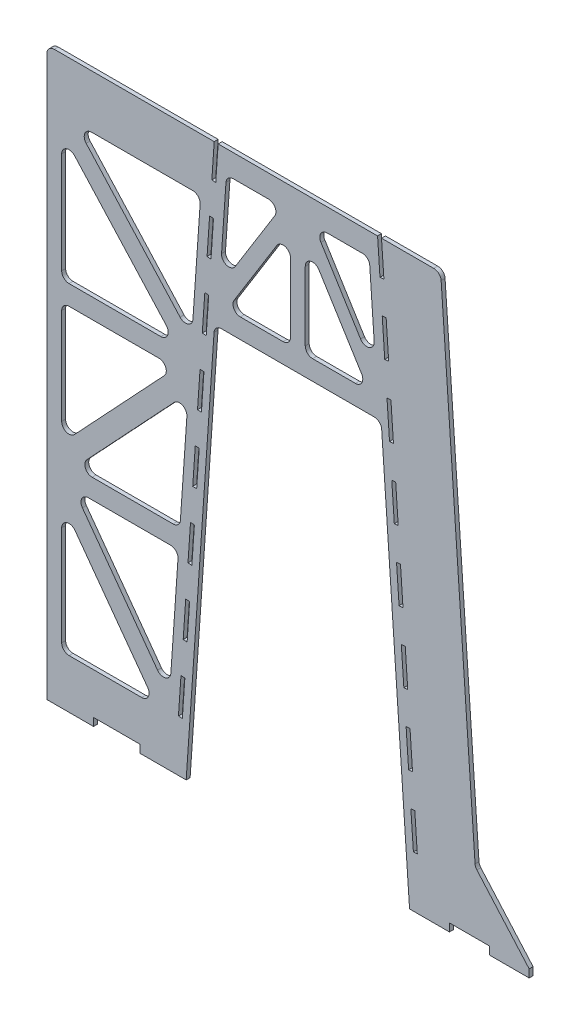
SolidWorks part; units mm, degrees
material "A-Glass Fiber"
ref_plane "Front Plane" through (0, 0, 0) normal (0, 0, 1) x (1, 0, 0)
ref_plane "Top Plane" through (0, 0, 0) normal (0, 1, 0) x (1, 0, 0)
ref_plane "Right Plane" through (0, 0, 0) normal (1, 0, 0) x (0, 0, -1)
sketch "Sketch1" plane through (0, 0, 0) normal (0, 0, 1) x (1, 0, 0)
  line L0 (-288.2759, 0) -> (288.2759, 0) construction
  line L1 (-215.8925, 1463.04) -> (215.8925, 1463.04)
  line L2 (0, 0) -> (0, 1733.4513) construction
  line L3 (19.05, 1104.9) -> (205.1391, 1104.9)
  line L4 (202.3135, 1145.5664) -> (41.4731, 1404.62)
  line L5 (205.1391, 1104.9) -> (19.05, 1404.62) construction
  line L6 (205.1391, 1104.9) -> (184.3133, 1404.62)
  line L7 (182.716, 1104.9) -> (19.05, 1368.5047)
  line L8 (19.05, 1404.62) -> (19.05, 1104.9)
  line L9 (184.3133, 1404.62) -> (19.05, 1404.62)
  line L10 (205.7153, 1463.04) -> (307.3735, 0)
  line L11 (317.5154, 0.5076) -> (215.8925, 1463.04)
  line L12 (317.5154, 0.5076) -> (317.5507, 0)
  line L13 (288.2759, 0) -> (215.0326, 1054.1)
  line L14 (476.8528, 0) -> (391.1675, 0) construction
  line L15 (266.6925, 1463.04) -> (368.5375, 1463.04)
  line L16 (368.5375, 1463.04) -> (457.7693, 178.8376)
  line L81 (215.8925, 1463.04) -> (266.6925, 1463.04)
  line L82 (-215.8925, 1463.04) -> (-647.7182, 1463.04)
  line L88 (317.5507, 0) -> (307.3718, 0)
  line L90 (215.0326, 1054.1) -> (-215.0326, 1054.1)
  line L92 (307.3718, 0) -> (288.2759, 0)
  line L93 (-288.2759, 0) -> (-215.0326, 1054.1)
  line L94 (-307.3735, 0) -> (-288.2759, 0)
  line L97 (-317.5507, 0) -> (-307.3735, 0)
  line L98 (-317.5154, 0.5076) -> (-317.5507, 0)
  line L99 (-317.5154, 0.5076) -> (-215.8925, 1463.04)
  line L100 (-205.7153, 1463.04) -> (-307.3735, 0)
  line L124 (-184.3133, 1404.62) -> (-19.05, 1404.62)
  line L125 (-19.05, 1404.62) -> (-19.05, 1104.9)
  line L126 (-182.716, 1104.9) -> (-19.05, 1368.5047)
  line L127 (-205.1391, 1104.9) -> (-19.05, 1404.62) construction
  line L128 (-202.3135, 1145.5664) -> (-41.4731, 1404.62)
  line L129 (-205.1391, 1104.9) -> (-184.3133, 1404.62)
  line L130 (-19.05, 1104.9) -> (-205.1391, 1104.9)
  line L131 (-317.5507, 0) -> (-647.7182, 0)
  line L132 (-647.7182, 0) -> (-647.7182, 1463.04)
  line L133 (-647.7182, 0) -> (-317.5507, 0)
  line L134 (-308.7262, 127) -> (-647.7182, 127)
  line L135 (-647.7182, 1325.88) -> (-225.423, 1325.88)
  line L136 (317.5507, 0) -> (368.3507, 0)
  line L137 (368.3507, 0) -> (266.6925, 1463.04)
  line L138 (368.3507, 0) -> (317.5507, 0)
  line L139 (-250.8842, 1325.88) -> (-334.1875, 127)
  line L140 (-609.6182, 127) -> (-609.6182, 1325.88)
  line L141 (-306.1844, 530.0133) -> (-609.6182, 530.0133)
  line L142 (-278.1813, 933.0267) -> (-609.6182, 933.0267)
  line L143 (-304.4195, 555.4133) -> (-609.6182, 555.4133)
  line L144 (-307.9493, 504.6133) -> (-609.6182, 504.6133)
  line L145 (-279.9462, 907.6267) -> (-609.6182, 907.6267)
  line L146 (-276.4164, 958.4267) -> (-609.6182, 958.4267)
  line L147 (-334.1875, 127) -> (-609.6182, 504.6133) construction
  line L148 (-609.6182, 555.4133) -> (-279.9462, 907.6267) construction
  line L149 (-276.4164, 958.4267) -> (-609.6182, 1325.88) construction
  line L150 (-331.453, 166.3535) -> (-578.1794, 504.6133)
  line L151 (-574.8276, 555.4133) -> (-282.736, 867.4768)
  line L152 (-273.976, 993.5478) -> (-575.3304, 1325.88)
  line L153 (-365.6263, 127) -> (-609.6182, 461.511)
  line L154 (-609.6182, 592.5827) -> (-314.7368, 907.6267)
  line L155 (-310.7042, 958.4267) -> (-609.6182, 1288.0676)
  line L156 (368.3507, 0) -> (596.9507, 0)
  line L157 (596.9507, 0) -> (596.9507, 20.32)
  line L158 (596.9507, 20.32) -> (347.1719, 304.8)
  point P0 (0, 0)
  point P3 (0, 0)
  point P106 (0, 0)
  point P118 (0, 1054.1)
  dimension "D6" = 25.4
  dimension "D7" = 50.8
  dimension "D8" = 58.42
  dimension "D9" = 19.05
  dimension "D10" = 647.7182
  dimension "D11" = 10.1527
  dimension "D12" = 25.4
  dimension "D13" = 25.4
  dimension "D14" = 25.4
  dimension "D15" = 25.4
  dimension "D16" = 25.4
  dimension "D17" = 25.4
  dimension "D18" = 1463.04
  dimension "D19" = 288.2759
  dimension "D20" = 29.2044
  dimension "D21" = 101.6
  dimension "D22" = 19.05
  dimension "D23" = 19.05
  dimension "D24" = 1054.1
  dimension "D25" = 20.32
  dimension "D37" = 127
  dimension "D38" = 50.8
  dimension "D39" = 25.4
  dimension "D40" = 38.1
  dimension "D41" = 403.0133
  dimension "D42" = 403.0133
  dimension "D43" = 25.4
  dimension "D44" = 25.4
  dimension "D45" = 25.4
  dimension "D46" = 25.4
  dimension "D47" = 279.4
  dimension "D48" = 304.8
  dimension "D49" = 50.8
  dimension "D52" = 137.16
extrude "Boss-Extrude1" add sketch "Sketch1" along normal blind 10.16
fillet "Fillet1" radius 19.05 35 edges at (-215.0326, 1054.1, 5.08) (215.0326, 1054.1, 5.08) (-202.3135, 1145.5664, 5.08) (-19.05, 1104.9, 5.08) (-182.716, 1104.9, 5.08) (-19.05, 1368.5047, 5.08) (-41.4731, 1404.62, 5.08) (-184.3133, 1404.62, 5.08) (-647.7182, 1463.04, 5.08) (-250.8842, 1325.88, 5.08) (-575.3304, 1325.88, 5.08) (-273.976, 993.5478, 5.08) (-609.6182, 958.4267, 5.08) (-609.6182, 1288.0676, 5.08) (-310.7042, 958.4267, 5.08) (-609.6182, 592.5827, 5.08) (-314.7368, 907.6267, 5.08) (-609.6182, 907.6267, 5.08) (-574.8276, 555.4133, 5.08) (-304.4195, 555.4133, 5.08) (-282.736, 867.4768, 5.08) (-307.9493, 504.6133, 5.08) (-331.453, 166.3535, 5.08) (-578.1794, 504.6133, 5.08) (-609.6182, 461.511, 5.08) (-365.6263, 127, 5.08) (-609.6182, 127, 5.08) (19.05, 1104.9, 5.08) (184.3133, 1404.62, 5.08) (41.4731, 1404.62, 5.08) (182.716, 1104.9, 5.08) (19.05, 1368.5047, 5.08) (202.3135, 1145.5664, 5.08) (457.7693, 178.8376, 5.08) (368.5375, 1463.04, 5.08)
sketch "Sketch2" plane through (0, 0, 10.16) normal (0, 0, 1) x (1, 0, 0)
  line L28 (215.8818, 1463.04) -> (205.7153, 1463.04) construction
  line L29 (205.7153, 1463.04) -> (211.9231, 1373.6642) construction
  line L30 (211.9231, 1373.6642) -> (222.0407, 1374.3669) construction
  line L31 (222.0407, 1374.3669) -> (215.8818, 1463.04) construction
  line L32 (217.7192, 1290.2141) -> (224.241, 1196.3181) construction
  line L33 (224.241, 1196.3181) -> (234.3587, 1197.0208) construction
  line L34 (234.3587, 1197.0208) -> (227.8369, 1290.9169) construction
  line L35 (227.8369, 1290.9169) -> (217.7192, 1290.2141) construction
  line L64 (230.039, 1112.8414) -> (236.5589, 1018.9719) construction
  line L65 (236.5589, 1018.9719) -> (246.6766, 1019.6747) construction
  line L66 (246.6766, 1019.6747) -> (240.1567, 1113.5442) construction
  line L67 (240.1567, 1113.5442) -> (230.039, 1112.8414) construction
  line L68 (242.3588, 935.4688) -> (248.8768, 841.6258) construction
  line L69 (248.8768, 841.6258) -> (258.9945, 842.3285) construction
  line L70 (258.9945, 842.3285) -> (252.4764, 936.1715) construction
  line L71 (252.4764, 936.1715) -> (242.3588, 935.4688) construction
  line L72 (254.6785, 758.0961) -> (261.1947, 664.2796) construction
  line L73 (261.1947, 664.2796) -> (271.3124, 664.9824) construction
  line L74 (271.3124, 664.9824) -> (264.7962, 758.7989) construction
  line L75 (264.7962, 758.7989) -> (254.6785, 758.0961) construction
  line L76 (266.9983, 580.7234) -> (273.5126, 486.9335) construction
  line L77 (273.5126, 486.9335) -> (283.6303, 487.6362) construction
  line L78 (283.6303, 487.6362) -> (277.1159, 581.4262) construction
  line L79 (277.1159, 581.4262) -> (266.9983, 580.7234) construction
  line L80 (279.318, 403.3508) -> (285.8305, 309.5874) construction
  line L81 (285.8305, 309.5874) -> (295.9482, 310.2901) construction
  line L82 (295.9482, 310.2901) -> (289.4357, 404.0535) construction
  line L83 (289.4357, 404.0535) -> (279.318, 403.3508) construction
  line L84 (291.6378, 225.9781) -> (298.1484, 132.2412) construction
  line L85 (298.1484, 132.2412) -> (308.2661, 132.944) construction
  line L86 (308.2661, 132.944) -> (301.7555, 226.6808) construction
  line L87 (301.7555, 226.6808) -> (291.6378, 225.9781) construction
  line L116 (215.8818, 1463.04) -> (205.7153, 1463.04)
  line L117 (205.7153, 1463.04) -> (211.9231, 1373.6642)
  line L118 (211.9231, 1373.6642) -> (222.0407, 1374.3669)
  line L119 (222.0407, 1374.3669) -> (215.8818, 1463.04)
  line L120 (217.7192, 1290.2141) -> (224.241, 1196.3181)
  line L121 (224.241, 1196.3181) -> (234.3587, 1197.0208)
  line L122 (234.3587, 1197.0208) -> (227.8369, 1290.9169)
  line L123 (227.8369, 1290.9169) -> (217.7192, 1290.2141)
  line L152 (230.039, 1112.8414) -> (236.5589, 1018.9719)
  line L153 (236.5589, 1018.9719) -> (246.6766, 1019.6747)
  line L154 (246.6766, 1019.6747) -> (240.1567, 1113.5442)
  line L155 (240.1567, 1113.5442) -> (230.039, 1112.8414)
  line L156 (242.3588, 935.4688) -> (248.8768, 841.6258)
  line L157 (248.8768, 841.6258) -> (258.9945, 842.3285)
  line L158 (258.9945, 842.3285) -> (252.4764, 936.1715)
  line L159 (252.4764, 936.1715) -> (242.3588, 935.4688)
  line L160 (254.6785, 758.0961) -> (261.1947, 664.2796)
  line L161 (261.1947, 664.2796) -> (271.3124, 664.9824)
  line L162 (271.3124, 664.9824) -> (264.7962, 758.7989)
  line L163 (264.7962, 758.7989) -> (254.6785, 758.0961)
  line L164 (266.9983, 580.7234) -> (273.5126, 486.9335)
  line L165 (273.5126, 486.9335) -> (283.6303, 487.6362)
  line L166 (283.6303, 487.6362) -> (277.1159, 581.4262)
  line L167 (277.1159, 581.4262) -> (266.9983, 580.7234)
  line L168 (279.318, 403.3508) -> (285.8305, 309.5874)
  line L169 (285.8305, 309.5874) -> (295.9482, 310.2901)
  line L170 (295.9482, 310.2901) -> (289.4357, 404.0535)
  line L171 (289.4357, 404.0535) -> (279.318, 403.3508)
  line L172 (291.6378, 225.9781) -> (298.1484, 132.2412)
  line L173 (298.1484, 132.2412) -> (308.2661, 132.944)
  line L174 (308.2661, 132.944) -> (301.7555, 226.6808)
  line L175 (301.7555, 226.6808) -> (291.6378, 225.9781)
  line L194 (-134.539, 20.32) -> (-288.2759, 20.32) construction
  line L195 (-647.7182, 0) -> (-527.4335, 0)
  line L196 (-647.7182, 0) -> (-647.7182, 20.32)
  line L197 (-647.7182, 20.32) -> (-527.4335, 20.32)
  line L198 (-527.4335, 0) -> (-527.4335, 20.32)
  line L199 (-288.2759, 0) -> (-216.2645, 1036.3705) construction
  line L200 (-527.4335, 0) -> (-407.1487, 0)
  line L201 (-527.4335, 0) -> (-527.4335, 20.32)
  line L202 (-527.4335, 20.32) -> (-407.1487, 20.32)
  line L203 (-407.1487, 0) -> (-407.1487, 20.32)
  line L204 (-407.1487, 0) -> (-286.864, 0)
  line L205 (-407.1487, 0) -> (-407.1487, 20.32)
  line L206 (-407.1487, 20.32) -> (-286.864, 20.32)
  line L207 (-286.864, 0) -> (-286.864, 20.32)
  line L213 (288.2759, 20.32) -> (134.539, 20.32) construction
  line L230 (288.2759, 0) -> (391.1675, 0)
  line L231 (288.2759, 0) -> (288.2759, 20.32)
  line L232 (288.2759, 20.32) -> (391.1675, 20.32)
  line L233 (391.1675, 0) -> (391.1675, 20.32)
  line L235 (391.1675, 0) -> (494.0591, 0)
  line L236 (391.1675, 0) -> (391.1675, 20.32)
  line L237 (391.1675, 20.32) -> (494.0591, 20.32)
  line L238 (494.0591, 0) -> (494.0591, 20.32)
  line L239 (494.0591, 0) -> (596.9507, 0)
  line L240 (494.0591, 0) -> (494.0591, 20.32)
  line L241 (494.0591, 20.32) -> (596.9507, 20.32)
  line L242 (596.9507, 0) -> (596.9507, 20.32)
  line L254 (-205.7153, 1463.04) -> (-215.8818, 1463.04) construction
  line L255 (-215.8818, 1463.04) -> (-222.0407, 1374.3669) construction
  line L256 (-222.0407, 1374.3669) -> (-211.9231, 1373.6642) construction
  line L257 (-211.9231, 1373.6642) -> (-205.7153, 1463.04) construction
  line L258 (-224.241, 1196.3181) -> (-217.7192, 1290.2141) construction
  line L259 (-217.7192, 1290.2141) -> (-227.8369, 1290.9169) construction
  line L260 (-227.8369, 1290.9169) -> (-234.3587, 1197.0208) construction
  line L261 (-234.3587, 1197.0208) -> (-224.241, 1196.3181) construction
  line L262 (-236.5589, 1018.9719) -> (-230.039, 1112.8414) construction
  line L263 (-230.039, 1112.8414) -> (-240.1567, 1113.5442) construction
  line L264 (-240.1567, 1113.5442) -> (-246.6766, 1019.6747) construction
  line L265 (-246.6766, 1019.6747) -> (-236.5589, 1018.9719) construction
  line L266 (-248.8768, 841.6258) -> (-242.3588, 935.4688) construction
  line L267 (-242.3588, 935.4688) -> (-252.4764, 936.1715) construction
  line L268 (-252.4764, 936.1715) -> (-258.9945, 842.3285) construction
  line L269 (-258.9945, 842.3285) -> (-248.8768, 841.6258) construction
  line L270 (-261.1947, 664.2796) -> (-254.6785, 758.0961) construction
  line L271 (-254.6785, 758.0961) -> (-264.7962, 758.7989) construction
  line L272 (-264.7962, 758.7989) -> (-271.3124, 664.9824) construction
  line L273 (-271.3124, 664.9824) -> (-261.1947, 664.2796) construction
  line L274 (-273.5126, 486.9335) -> (-266.9983, 580.7234) construction
  line L275 (-266.9983, 580.7234) -> (-277.1159, 581.4262) construction
  line L276 (-277.1159, 581.4262) -> (-283.6303, 487.6362) construction
  line L277 (-283.6303, 487.6362) -> (-273.5126, 486.9335) construction
  line L278 (-285.8305, 309.5874) -> (-279.318, 403.3508) construction
  line L279 (-279.318, 403.3508) -> (-289.4357, 404.0535) construction
  line L280 (-289.4357, 404.0535) -> (-295.9482, 310.2901) construction
  line L281 (-295.9482, 310.2901) -> (-285.8305, 309.5874) construction
  line L282 (-298.1484, 132.2412) -> (-291.6378, 225.9781) construction
  line L283 (-291.6378, 225.9781) -> (-301.7555, 226.6808) construction
  line L284 (-301.7555, 226.6808) -> (-308.2661, 132.944) construction
  line L285 (-308.2661, 132.944) -> (-298.1484, 132.2412) construction
  line L298 (-205.7153, 1463.04) -> (-215.8818, 1463.04)
  line L299 (-215.8818, 1463.04) -> (-222.0407, 1374.3669)
  line L300 (-222.0407, 1374.3669) -> (-211.9231, 1373.6642)
  line L301 (-211.9231, 1373.6642) -> (-205.7153, 1463.04)
  line L302 (-224.241, 1196.3181) -> (-217.7192, 1290.2141)
  line L303 (-217.7192, 1290.2141) -> (-227.8369, 1290.9169)
  line L304 (-227.8369, 1290.9169) -> (-234.3587, 1197.0208)
  line L305 (-234.3587, 1197.0208) -> (-224.241, 1196.3181)
  line L306 (-236.5589, 1018.9719) -> (-230.039, 1112.8414)
  line L307 (-230.039, 1112.8414) -> (-240.1567, 1113.5442)
  line L308 (-240.1567, 1113.5442) -> (-246.6766, 1019.6747)
  line L309 (-246.6766, 1019.6747) -> (-236.5589, 1018.9719)
  line L310 (-248.8768, 841.6258) -> (-242.3588, 935.4688)
  line L311 (-242.3588, 935.4688) -> (-252.4764, 936.1715)
  line L312 (-252.4764, 936.1715) -> (-258.9945, 842.3285)
  line L313 (-258.9945, 842.3285) -> (-248.8768, 841.6258)
  line L314 (-261.1947, 664.2796) -> (-254.6785, 758.0961)
  line L315 (-254.6785, 758.0961) -> (-264.7962, 758.7989)
  line L316 (-264.7962, 758.7989) -> (-271.3124, 664.9824)
  line L317 (-271.3124, 664.9824) -> (-261.1947, 664.2796)
  line L318 (-273.5126, 486.9335) -> (-266.9983, 580.7234)
  line L319 (-266.9983, 580.7234) -> (-277.1159, 581.4262)
  line L320 (-277.1159, 581.4262) -> (-283.6303, 487.6362)
  line L321 (-283.6303, 487.6362) -> (-273.5126, 486.9335)
  line L322 (-285.8305, 309.5874) -> (-279.318, 403.3508)
  line L323 (-279.318, 403.3508) -> (-289.4357, 404.0535)
  line L324 (-289.4357, 404.0535) -> (-295.9482, 310.2901)
  line L325 (-295.9482, 310.2901) -> (-285.8305, 309.5874)
  line L326 (-298.1484, 132.2412) -> (-291.6378, 225.9781)
  line L327 (-291.6378, 225.9781) -> (-301.7555, 226.6808)
  line L328 (-301.7555, 226.6808) -> (-308.2661, 132.944)
  line L329 (-308.2661, 132.944) -> (-298.1484, 132.2412)
extrude "Cut-Extrude1" cut sketch "Sketch2" against normal blind 12.7 contours L200 L203 L202 L198 | L235 L238 L237 L233 | L118 L119 L116 L117 | L122 L123 L120 L121 | L154 L155 L152 L153 | L158 L159 L156 L157 | L162 L163 L160 L161 | L166 L167 L164 L165 | L170 L171 L168 L169 | L174 L175 L172 L173 | L328 L329 L326 L327 | L324 L325 L322 L323 | L320 L321 L318 L319 | L316 L317 L314 L315 | L312 L313 L310 L311 | L308 L309 L306 L307 | L304 L305 L302 L303 | L300 L301 L298 L299
sketch "Sketch4" [suppressed] plane through (0, 0, 10.16) normal (0, 0, 1) x (1, 0, 0)
  line L0 (596.9507, 0) -> (494.0591, 0) construction
  line L1 (596.9507, 0) -> (596.9507, 20.32) construction
  line L2 (596.9507, 0) -> (494.0591, 0)
  line L3 (596.9507, 0) -> (596.9507, 20.32)
  line L4 (337.4418, 445.6368) -> (336.7375, 455.7724)
  line L5 (337.4418, 445.6368) -> (286.7919, 442.1174)
  line L6 (336.7375, 455.7724) -> (286.0876, 452.253)
  line L7 (286.7919, 442.1174) -> (286.0876, 452.253)
  line L8 (388.0923, 449.1521) -> (387.388, 459.2876)
  line L9 (388.0923, 449.1521) -> (438.7422, 452.6714)
  line L10 (387.388, 459.2876) -> (438.0379, 462.807)
  line L11 (438.7422, 452.6714) -> (438.0379, 462.807)
  line L12 (369.7694, 1445.3105) -> (457.3235, 185.2533) construction
  point P2 (596.9507, 0)
